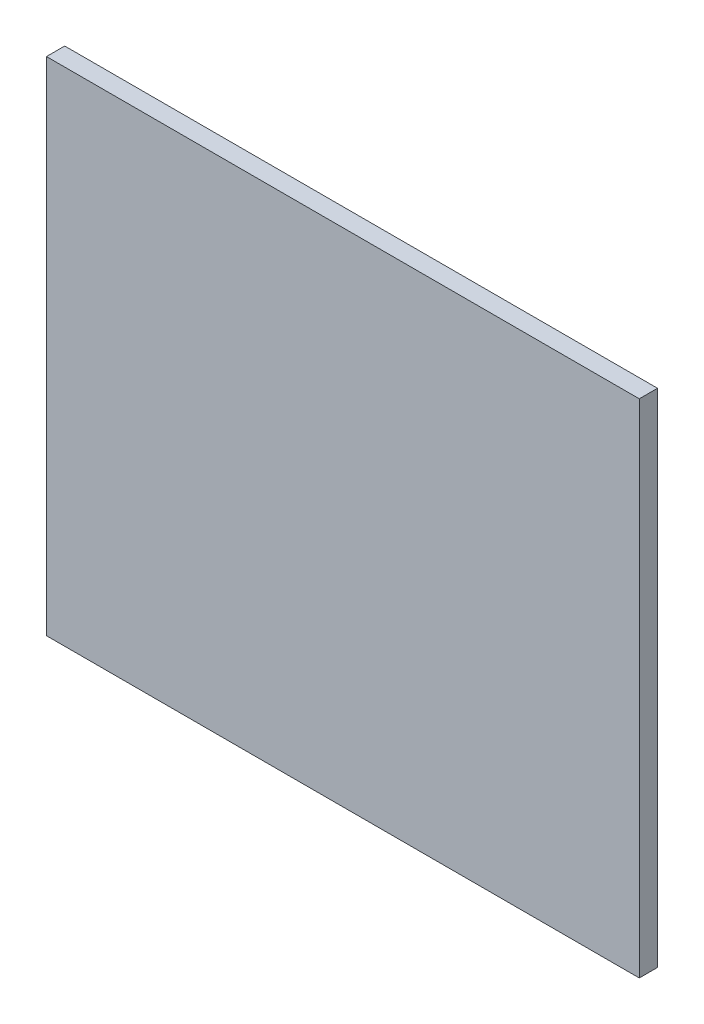
SolidWorks part; units mm, degrees
material "AISI Type 316L stainless steel"
ref_plane "Front Plane" through (0, 0, 0) normal (0, 0, 1) x (1, 0, 0)
ref_plane "Top Plane" through (0, 0, 0) normal (0, 1, 0) x (1, 0, 0)
ref_plane "Right Plane" through (0, 0, 0) normal (1, 0, 0) x (0, 0, -1)
sketch "Extrude sketch 1" plane through (0, 0, 0) normal (0, 0, 1) x (1, 0, 0)
  line L0 (55, -55) -> (185, -55)
  line L1 (185, -55) -> (185, 55)
  line L2 (185, 55) -> (55, 55)
  line L3 (55, 55) -> (55, -55)
  dimension "D1" = 130
  dimension "D2" = 110
extrude "Extrude 1" add sketch "Extrude sketch 1" along normal blind 4 from offset 36 separate body
